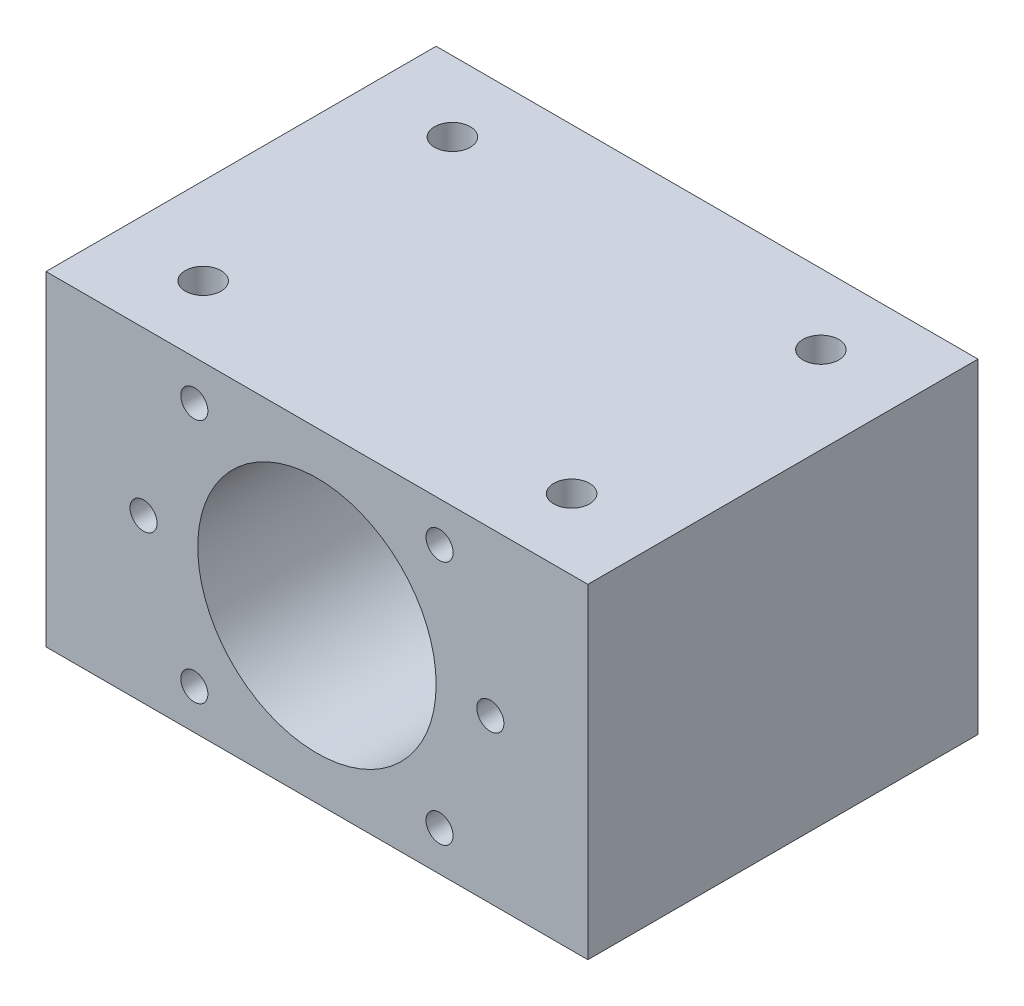
SolidWorks part; units mm, degrees
ref_plane "前视基准面" through (0, 0, 0) normal (0, 0, 1) x (1, 0, 0)
ref_plane "上视基准面" through (0, 0, 0) normal (0, 1, 0) x (1, 0, 0)
ref_plane "右视基准面" through (0, 0, 0) normal (1, 0, 0) x (0, 0, -1)
sketch "草图1" plane through (0, 0, 0) normal (0, 0, 1) x (1, 0, 0)
  line L1 (-25, 15) -> (25, 15)
  line L2 (-25, 15) -> (-25, -15)
  line L3 (-25, -15) -> (25, -15)
  line L4 (25, 15) -> (25, -15)
  line L5 (-25, 15) -> (25, -15) construction
  line L6 (-25, -15) -> (25, 15) construction
  circle A0 centre (0, 0) radius 11
  point P0 (0, 0)
  dimension "D1" = 50
  dimension "D2" = 30
extrude "凸台-拉伸1" add sketch "草图1" along normal mid plane 36
sketch "草图2" plane through (0, 0, 18) normal (0, 0, 1) x (1, 0, 0)
  circle A0 centre (0, 0) radius 16 construction
  circle A1 centre (-16, 0) radius 2
  circle A2 centre (-11.3137, 11.3137) radius 2
  circle A4 centre (11.3137, 11.3137) radius 2
  circle A5 centre (16, 0) radius 2
  circle A6 centre (11.3137, -11.3137) radius 2
  circle A8 centre (-11.3137, -11.3137) radius 2
  circle A9 centre (0, 16) radius 2
  circle A10 centre (0, -16) radius 2
  point P21 (0, 0)
  dimension "D1" = 8
hole_wizard "M3 螺纹孔的螺纹孔钻头1" positions "3D草图2" profile "草图4" hole size "M3" standard "GB" end condition through all
sketch3d "3D草图2"
  point P0 (-16, 0, 18)
  point P3 (-11.3137, 11.3137, 18)
  point P6 (11.3137, 11.3137, 18)
  point P9 (16, 0, 18)
  point P12 (11.3137, -11.3137, 18)
  point P15 (-11.3137, -11.3137, 18)
sketch "草图4" plane through (-16, 0, 18) normal (1, 0, 0) x (0, -1, 0)
  line L0 (0, 0) -> (0, 36)
  line L1 (0, 36) -> (1.25, 36)
  line L2 (1.25, 36) -> (1.25, 0)
  line L5 (1.25, 0) -> (0, 0)
  line L11 (0, -6.35) -> (0, 107.95) construction
  dimension "通孔孔直径" = 2.5
  dimension "通孔孔深度" = 36
sketch "草图5" plane through (0, 15, 0) normal (0, 1, 0) x (1, 0, 0)
  line L0 (-1000, 0) -> (49000, 0) construction
  line L1 (0, -1000) -> (0, 49000) construction
  circle A0 centre (-17, 11.5) radius 2
  dimension "D1" = 17
  dimension "D2" = 11.5
hole_wizard "M4 螺纹孔的螺纹孔钻头1" positions "3D草图3" profile "草图6" hole size "M4" standard "GB" end condition through all
sketch3d "3D草图3"
  point P0 (-17, 15, -11.5)
sketch "草图6" plane through (-17, 15, -11.5) normal (1, 0, 0) x (0, 0, 1)
  line L0 (0, 0) -> (0, 30)
  line L1 (0, 30) -> (1.65, 30)
  line L2 (1.65, 30) -> (1.65, 0)
  line L5 (1.65, 0) -> (0, 0)
  line L11 (0, -6.35) -> (0, 107.95) construction
  dimension "通孔孔直径" = 3.3
  dimension "通孔孔深度" = 30
mirror "镜向1" about plane through (0, 0, 0) normal (1, 0, 0) of "M4 螺纹孔的螺纹孔钻头1"
mirror "镜向2" about plane through (0, 0, 0) normal (0, 0, 1) of "镜向1", "M4 螺纹孔的螺纹孔钻头1"
